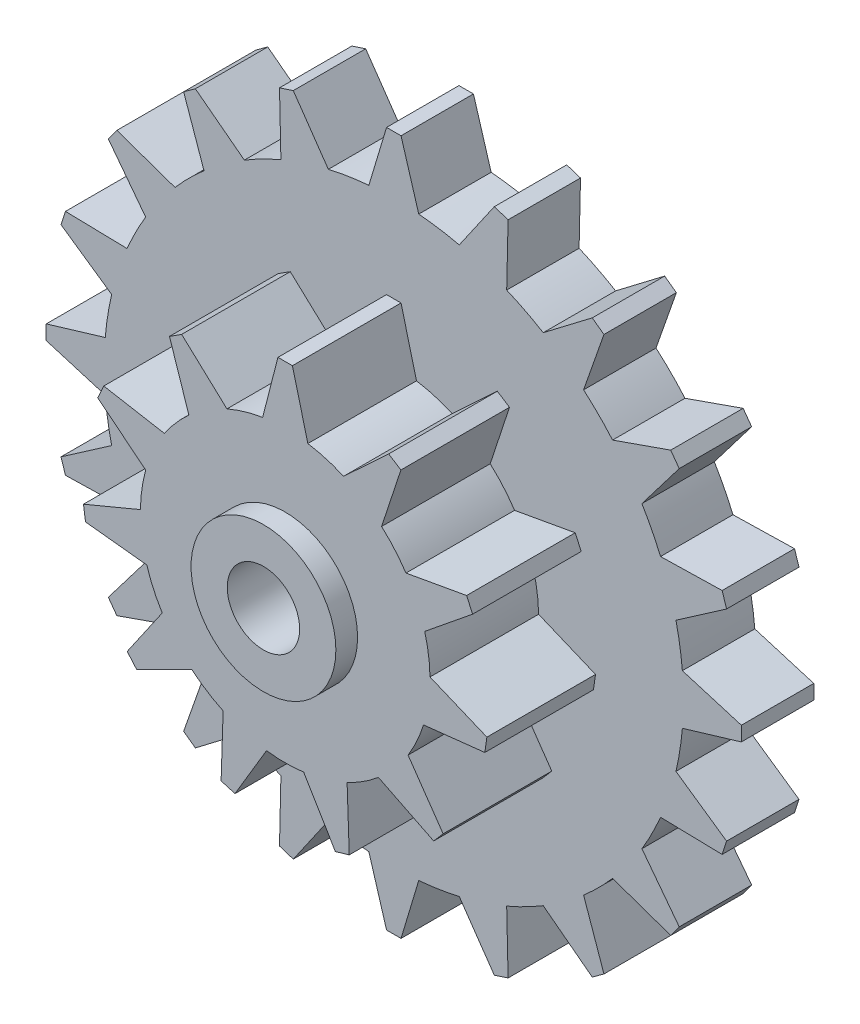
SolidWorks part; units mm, degrees
ref_plane "Front Plane" through (0, 0, 0) normal (0, 0, 1) x (1, 0, 0)
ref_plane "Top Plane" through (0, 0, 0) normal (0, 1, 0) x (1, 0, 0)
ref_plane "Right Plane" through (0, 0, 0) normal (1, 0, 0) x (0, 0, -1)
sketch "Sketch1" plane through (0, 0, 0) normal (0, 0, 1) x (1, 0, 0)
  circle A0 centre (0, 0) radius 40
  dimension "D1" = 80
extrude "Boss-Extrude1" add sketch "Sketch1" along normal blind 10
sketch "Sketch2" plane through (0, 0, 10) normal (0, 0, 1) x (1, 0, 0)
  line L0 (0, 0) -> (0, 40) construction
  line L1 (0, 40) -> (0, 48) construction
  line L2 (-1, 48) -> (1, 48)
  line L3 (1, 48) -> (4, 38)
  line L4 (4, 38) -> (-4, 38)
  line L5 (-4, 38) -> (-1, 48)
  line L6 (0, 40) -> (0, 38)
  line L7 (7.9384, 37.3762) -> (13.8818, 45.9597)
  line L8 (13.8818, 45.9597) -> (15.7839, 45.3417)
  line L9 (15.7839, 45.3417) -> (15.5469, 34.9041)
  line L10 (15.5469, 34.9041) -> (7.9384, 37.3762)
  line L11 (19.0998, 33.0938) -> (27.4047, 39.4206)
  line L12 (27.4047, 39.4206) -> (29.0227, 38.245)
  line L13 (29.0227, 38.245) -> (25.5719, 28.3915)
  line L14 (25.5719, 28.3915) -> (19.0998, 33.0938)
  line L15 (28.3915, 25.5719) -> (38.245, 29.0227)
  line L16 (38.245, 29.0227) -> (39.4206, 27.4047)
  line L17 (39.4206, 27.4047) -> (33.0938, 19.0998)
  line L18 (33.0938, 19.0998) -> (28.3915, 25.5719)
  line L19 (34.9041, 15.5469) -> (45.3417, 15.7839)
  line L20 (45.3417, 15.7839) -> (45.9597, 13.8818)
  line L21 (45.9597, 13.8818) -> (37.3762, 7.9384)
  line L22 (37.3762, 7.9384) -> (34.9041, 15.5469)
  line L23 (38, 4) -> (48, 1)
  line L24 (48, 1) -> (48, -1)
  line L25 (48, -1) -> (38, -4)
  line L26 (38, -4) -> (38, 4)
  line L27 (37.3762, -7.9384) -> (45.9597, -13.8818)
  line L28 (45.9597, -13.8818) -> (45.3417, -15.7839)
  line L29 (45.3417, -15.7839) -> (34.9041, -15.5469)
  line L30 (34.9041, -15.5469) -> (37.3762, -7.9384)
  line L31 (33.0938, -19.0998) -> (39.4206, -27.4047)
  line L32 (39.4206, -27.4047) -> (38.245, -29.0227)
  line L33 (38.245, -29.0227) -> (28.3915, -25.5719)
  line L34 (28.3915, -25.5719) -> (33.0938, -19.0998)
  line L35 (25.5719, -28.3915) -> (29.0227, -38.245)
  line L36 (29.0227, -38.245) -> (27.4047, -39.4206)
  line L37 (27.4047, -39.4206) -> (19.0998, -33.0938)
  line L38 (19.0998, -33.0938) -> (25.5719, -28.3915)
  line L39 (15.5469, -34.9041) -> (15.7839, -45.3417)
  line L40 (15.7839, -45.3417) -> (13.8818, -45.9597)
  line L41 (13.8818, -45.9597) -> (7.9384, -37.3762)
  line L42 (7.9384, -37.3762) -> (15.5469, -34.9041)
  line L43 (4, -38) -> (1, -48)
  line L44 (1, -48) -> (-1, -48)
  line L45 (-1, -48) -> (-4, -38)
  line L46 (-4, -38) -> (4, -38)
  line L47 (-7.9384, -37.3762) -> (-13.8818, -45.9597)
  line L48 (-13.8818, -45.9597) -> (-15.7839, -45.3417)
  line L49 (-15.7839, -45.3417) -> (-15.5469, -34.9041)
  line L50 (-15.5469, -34.9041) -> (-7.9384, -37.3762)
  line L51 (-19.0998, -33.0938) -> (-27.4047, -39.4206)
  line L52 (-27.4047, -39.4206) -> (-29.0227, -38.245)
  line L53 (-29.0227, -38.245) -> (-25.5719, -28.3915)
  line L54 (-25.5719, -28.3915) -> (-19.0998, -33.0938)
  line L55 (-28.3915, -25.5719) -> (-38.245, -29.0227)
  line L56 (-38.245, -29.0227) -> (-39.4206, -27.4047)
  line L57 (-39.4206, -27.4047) -> (-33.0938, -19.0998)
  line L58 (-33.0938, -19.0998) -> (-28.3915, -25.5719)
  line L59 (-34.9041, -15.5469) -> (-45.3417, -15.7839)
  line L60 (-45.3417, -15.7839) -> (-45.9597, -13.8818)
  line L61 (-45.9597, -13.8818) -> (-37.3762, -7.9384)
  line L62 (-37.3762, -7.9384) -> (-34.9041, -15.5469)
  line L63 (-38, -4) -> (-48, -1)
  line L64 (-48, -1) -> (-48, 1)
  line L65 (-48, 1) -> (-38, 4)
  line L66 (-38, 4) -> (-38, -4)
  line L67 (-37.3762, 7.9384) -> (-45.9597, 13.8818)
  line L68 (-45.9597, 13.8818) -> (-45.3417, 15.7839)
  line L69 (-45.3417, 15.7839) -> (-34.9041, 15.5469)
  line L70 (-34.9041, 15.5469) -> (-37.3762, 7.9384)
  line L71 (-33.0938, 19.0998) -> (-39.4206, 27.4047)
  line L72 (-39.4206, 27.4047) -> (-38.245, 29.0227)
  line L73 (-38.245, 29.0227) -> (-28.3915, 25.5719)
  line L74 (-28.3915, 25.5719) -> (-33.0938, 19.0998)
  line L75 (-25.5719, 28.3915) -> (-29.0227, 38.245)
  line L76 (-29.0227, 38.245) -> (-27.4047, 39.4206)
  line L77 (-27.4047, 39.4206) -> (-19.0998, 33.0938)
  line L78 (-19.0998, 33.0938) -> (-25.5719, 28.3915)
  line L79 (-15.5469, 34.9041) -> (-15.7839, 45.3417)
  line L80 (-15.7839, 45.3417) -> (-13.8818, 45.9597)
  line L81 (-13.8818, 45.9597) -> (-7.9384, 37.3762)
  line L82 (-7.9384, 37.3762) -> (-15.5469, 34.9041)
  circle A0 centre (0, 0) radius 40 construction
  point P10 (0, 48)
  point P92 (0, 0)
  dimension "D1" = 2
  dimension "D2" = 8
  dimension "D3" = 2
  dimension "D4" = 8
  dimension "D5" = 20
extrude "Boss-Extrude2" add sketch "Sketch2" against normal blind 10 contours L5 L2 L3 L4 | L79 L80 L81 L82 | L75 L76 L77 L78 | L71 L72 L73 L74 | L67 L68 L69 L70 | L63 L64 L65 L66 | L59 L60 L61 L62 | L55 L56 L57 L58 | L51 L52 L53 L54 | L47 L48 L49 L50 | L43 L44 L45 L46 | L39 L40 L41 L42 | L35 L36 L37 L38 | L31 L32 L33 L34 | L27 L28 L29 L30 | L23 L24 L25 L26 | L19 L20 L21 L22 | L15 L16 L17 L18 | L11 L12 L13 L14 | L7 L8 L9 L10
sketch "Sketch3" plane through (0, 0, 10) normal (0, 0, 1) x (1, 0, 0)
  circle A0 centre (0, 0) radius 20
  dimension "D1" = 40
extrude "Boss-Extrude3" add sketch "Sketch3" along normal blind 15
sketch "Sketch4" plane through (0, 0, 25) normal (0, 0, 1) x (1, 0, 0)
  line L0 (0, 0) -> (0, 20) construction
  line L1 (0, 20) -> (0, 28) construction
  line L2 (-1, 28) -> (1, 28)
  line L3 (1, 28) -> (3.9996, 16.3982)
  line L4 (3.9996, 16.3982) -> (-3.9996, 16.2909)
  line L5 (-3.9996, 16.2909) -> (-1, 28)
  line L6 (0, 20) -> (0, 16.3445)
  line L7 (5.4428, 15.8671) -> (14.2967, 24.0957)
  line L8 (14.2967, 24.0957) -> (15.9792, 23.0145)
  line L9 (15.9792, 23.0145) -> (12.2302, 11.6327)
  line L10 (12.2302, 11.6327) -> (5.4428, 15.8671)
  line L11 (13.1572, 10.4057) -> (25.0543, 12.5413)
  line L12 (25.0543, 12.5413) -> (25.8851, 10.722)
  line L13 (25.8851, 10.722) -> (16.5778, 3.1739)
  line L14 (16.5778, 3.1739) -> (13.1572, 10.4057)
  line L15 (16.6943, 1.6405) -> (27.8573, -2.995)
  line L16 (27.8573, -2.995) -> (27.5727, -4.9746)
  line L17 (27.5727, -4.9746) -> (15.6621, -6.2926)
  line L18 (15.6621, -6.2926) -> (16.6943, 1.6405)
  line L19 (14.931, -7.6455) -> (21.8158, -17.5804)
  line L20 (21.8158, -17.5804) -> (20.5061, -19.0919)
  line L21 (20.5061, -19.0919) -> (9.7737, -13.7613)
  line L22 (9.7737, -13.7613) -> (14.931, -7.6455)
  line L23 (8.4273, -14.5042) -> (8.848, -26.5841)
  line L24 (8.848, -26.5841) -> (6.929, -27.1475)
  line L25 (6.929, -27.1475) -> (0.7823, -16.8608)
  line L26 (0.7823, -16.8608) -> (8.4273, -14.5042)
  line L27 (-0.7521, -16.7578) -> (-6.929, -27.1475)
  line L28 (-6.929, -27.1475) -> (-8.848, -26.5841)
  line L29 (-8.848, -26.5841) -> (-8.4575, -14.6071)
  line L30 (-8.4575, -14.6071) -> (-0.7521, -16.7578)
  line L31 (-9.6926, -13.691) -> (-20.5061, -19.0919)
  line L32 (-20.5061, -19.0919) -> (-21.8158, -17.5804)
  line L33 (-21.8158, -17.5804) -> (-15.0121, -7.7158)
  line L34 (-15.0121, -7.7158) -> (-9.6926, -13.691)
  line L35 (-15.5559, -6.2774) -> (-27.5727, -4.9746)
  line L36 (-27.5727, -4.9746) -> (-27.8573, -2.995)
  line L37 (-27.8573, -2.995) -> (-16.8005, 1.6252)
  line L38 (-16.8005, 1.6252) -> (-15.5559, -6.2774)
  line L39 (-16.4802, 3.1293) -> (-25.8851, 10.722)
  line L40 (-25.8851, 10.722) -> (-25.0543, 12.5413)
  line L41 (-25.0543, 12.5413) -> (-13.2548, 10.4503)
  line L42 (-13.2548, 10.4503) -> (-16.4802, 3.1293)
  line L43 (-12.1722, 11.5424) -> (-15.9792, 23.0145)
  line L44 (-15.9792, 23.0145) -> (-14.2967, 24.0957)
  line L45 (-14.2967, 24.0957) -> (-5.5008, 15.9574)
  line L46 (-5.5008, 15.9574) -> (-12.1722, 11.5424)
  circle A0 centre (0, 0) radius 20 construction
  point P10 (0, 28)
  point P56 (0, 0)
  circle M5 centre (0, 0) radius 20
  dimension "D1" = 2
  dimension "D2" = 8
  dimension "D3" = 8
  dimension "D4" = 3.6555
  dimension "D5" = 11
extrude "Boss-Extrude4" add sketch "Sketch4" against normal blind 15 contours L45 L44 L43 M5 | L5 L3 L2 M5 | L9 L8 L7 M5 | L13 L12 L11 M5 | L17 L16 L15 M5 | L41 L40 L39 M5 | L37 L36 L35 M5 | L33 L32 L31 M5 | L29 L28 L27 M5 | L25 L24 L23 M5 | L21 L20 L19 M5
sketch "Sketch5" plane through (0, 0, 25) normal (0, 0, 1) x (1, 0, 0)
  circle A0 centre (0, 0) radius 5
  circle A1 centre (0, 0) radius 10
  dimension "D1" = 10
  dimension "D2" = 5
extrude "Boss-Extrude6" add sketch "Sketch5" along normal blind 3 and the other way blind 28
sketch "Sketch6" plane through (0, 0, 25) normal (0, 0, 1) x (1, 0, 0)
  circle A1 centre (0, 0) radius 5
  dimension "D1" = 10
extrude "Cut-Extrude1" cut sketch "Sketch6" against normal through all both and the other way through all
